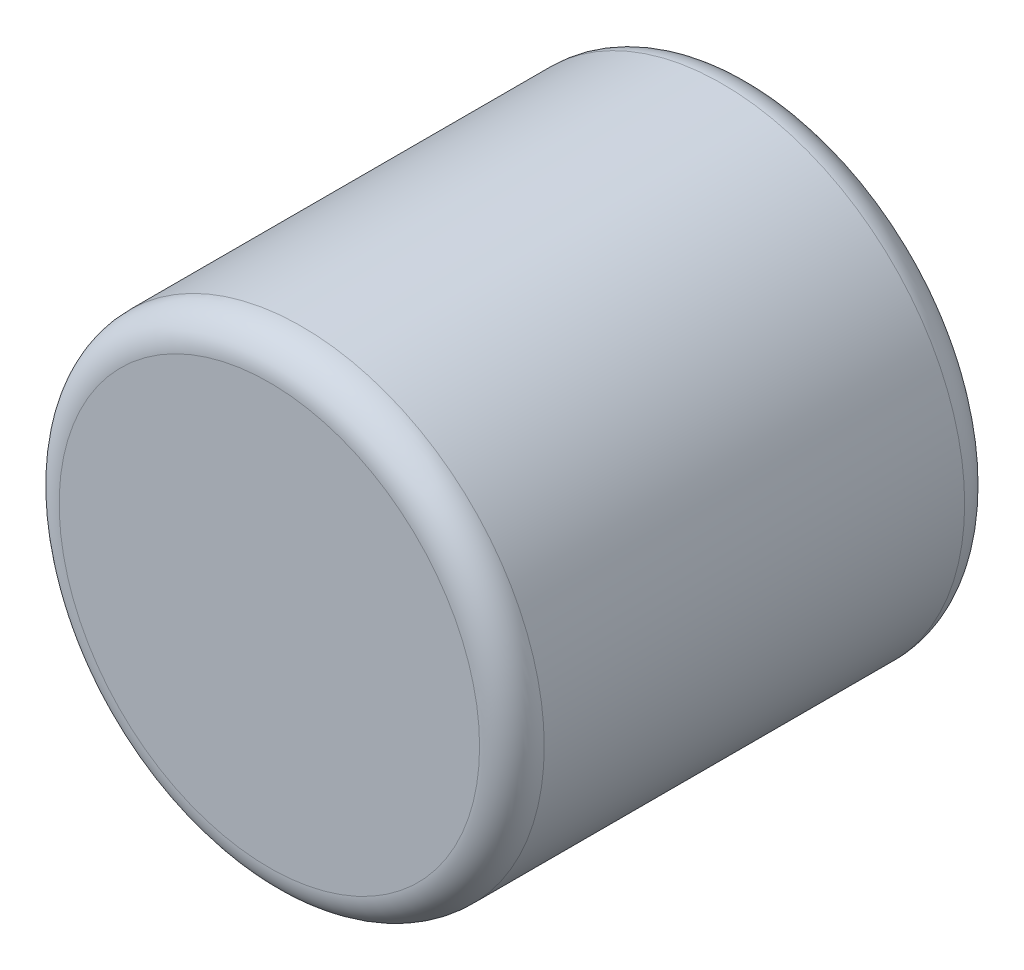
SolidWorks part; units mm, degrees
ref_plane "Front Plane" through (0, 0, 0) normal (0, 0, 1) x (1, 0, 0)
ref_plane "Top Plane" through (0, 0, 0) normal (0, 1, 0) x (1, 0, 0)
ref_plane "Right Plane" through (0, 0, 0) normal (1, 0, 0) x (0, 0, -1)
sketch "Sketch1" plane through (0, 0, 0) normal (0, 0, 1) x (1, 0, 0)
  circle A0 centre (0, 0) radius 1.5
  dimension "D1" = 3
extrude "Boss-Extrude1" add sketch "Sketch1" along normal blind 3
fillet "Fillet1" radius 0.2 2 edges at (1.5, 0, 3) (1.5, 0, 0)
